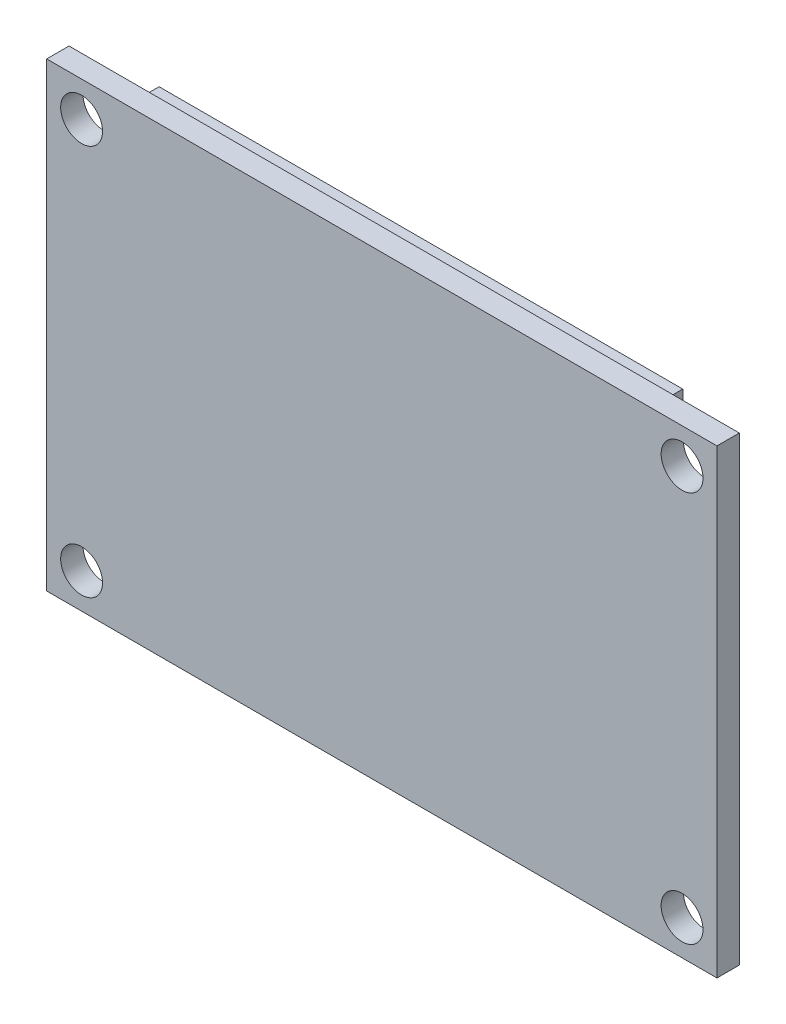
SolidWorks part; units mm, degrees
ref_plane "Plan de face" through (0, 0, 0) normal (0, 0, 1) x (1, 0, 0)
ref_plane "Plan de dessus" through (0, 0, 0) normal (0, 1, 0) x (1, 0, 0)
ref_plane "Plan de droite" through (0, 0, 0) normal (1, 0, 0) x (0, 0, -1)
sketch "BASE PCB" plane through (0, 0, 0) normal (0, 0, 1) x (1, 0, 0)
  line L0 (0, -18.15) -> (0, 18.15) construction
  line L1 (24, 16.5) -> (-24, 16.5)
  line L2 (24, 16.5) -> (24, -16.5)
  line L3 (24, -16.5) -> (-24, -16.5)
  line L4 (-24, 16.5) -> (-24, -16.5)
  line L5 (24, 16.5) -> (-24, -16.5) construction
  line L6 (24, -16.5) -> (-24, 16.5) construction
  line L8 (24, 10) -> (18, 10) construction
  line L9 (24, 10) -> (24, -10) construction
  line L10 (24, -10) -> (18, -10) construction
  line L11 (18, 10) -> (18, -10) construction
  circle A0 centre (-21.5, 14) radius 1.5
  circle A1 centre (-21.5, -14) radius 1.5
  circle A2 centre (21.5, -14) radius 1.5
  circle A3 centre (21.5, 14) radius 1.5
  point P0 (0, 0)
  point P10 (24, 0)
  point P21 (24, 0)
  dimension "D3" = 3
  dimension "D4" = 2.5
  dimension "D1" = 48
  dimension "D2" = 33
  dimension "D5" = 2.5
  dimension "D6" = 2.5
  dimension "D7" = 6
  dimension "D8" = 20
extrude "Boss.-Extru.1" add sketch "BASE PCB" along normal blind 1.6
sketch "Esquisse4" plane through (0, 0, 0) normal (0, 0, 1) x (1, 0, 0)
  line L1 (18.75, 16) -> (-18.75, 16)
  line L2 (18.75, 16) -> (18.75, -16)
  line L3 (18.75, -16) -> (-18.75, -16)
  line L4 (-18.75, 16) -> (-18.75, -16)
  line L5 (18.75, 16) -> (-18.75, -16) construction
  line L6 (18.75, -16) -> (-18.75, 16) construction
  point P0 (0, 0)
  dimension "D1" = 32
  dimension "D2" = 37.5
extrude "Boss.-Extru.2" add sketch "Esquisse4" against normal blind 1.2
sketch "Esquisse5" plane through (0, 0, -1.2) normal (0, 0, -1) x (-1, 0, 0)
  line L1 (-16.75, -13.8) -> (10.85, -13.8)
  line L2 (-16.75, -13.8) -> (-16.75, 13.8)
  line L3 (-16.75, 13.8) -> (10.85, 13.8)
  line L4 (10.85, -13.8) -> (10.85, 13.8)
  line L7 (-18.75, -16) -> (-18.75, 16) construction
  point P6 (10.85, 0)
  dimension "D1" = 27.6
  dimension "D2" = 2
extrude "Enlèv. mat.-Extru.2" cut sketch "Esquisse5" against normal blind 0.5
